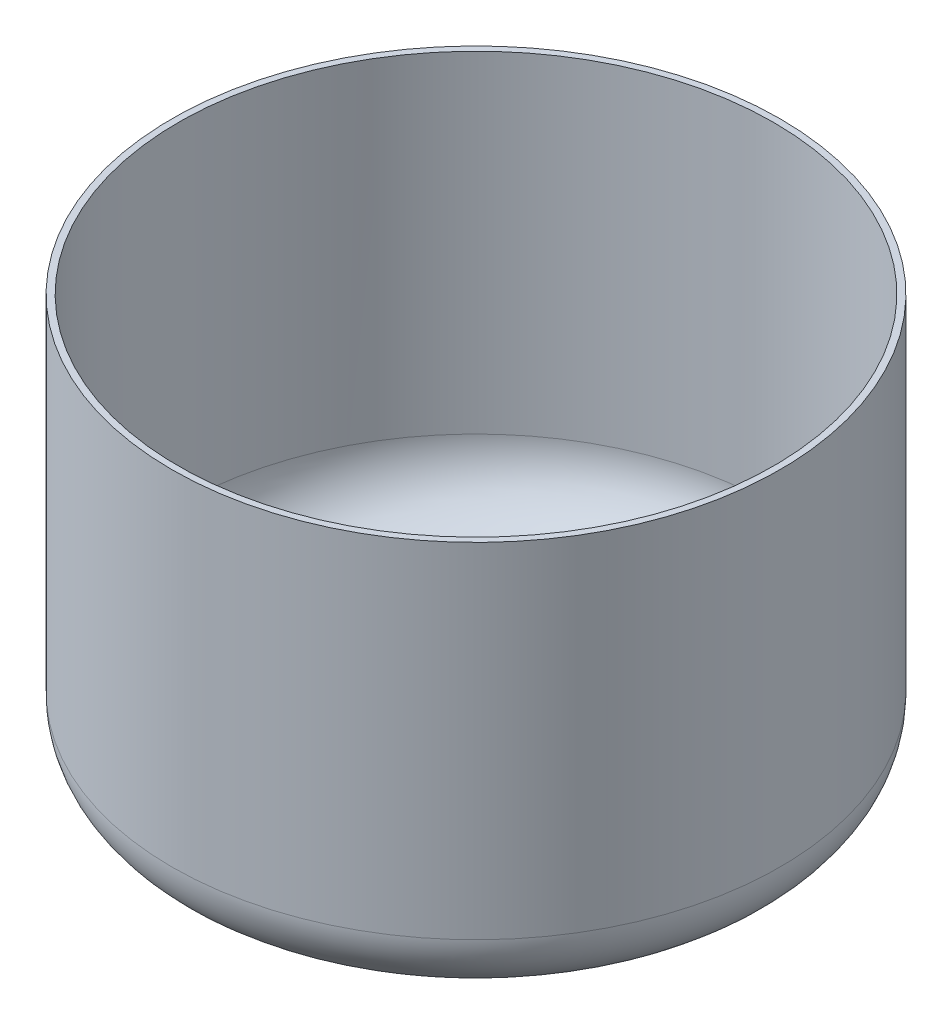
SolidWorks part; units mm, degrees
ref_plane "Front Plane" through (0, 0, 0) normal (0, 0, 1) x (1, 0, 0)
ref_plane "Top Plane" through (0, 0, 0) normal (0, 1, 0) x (1, 0, 0)
ref_plane "Right Plane" through (0, 0, 0) normal (1, 0, 0) x (0, 0, -1)
sketch "Compartment" plane through (0, 0, 0) normal (0, 0, 1) x (1, 0, 0)
  line L3 (120.65, -80) -> (0, -80)
  line L6 (118.11, 81.972) -> (120.65, 81.972)
  line L9 (118.11, 81.972) -> (118.11, -75)
  line L10 (118.11, -75) -> (0, -75)
  line L11 (0, -75) -> (0, -80)
  line L14 (120.65, 81.972) -> (120.65, -80)
  dimension "D1" = 156.972
  dimension "D2" = 2.54
  dimension "D5" = 118.11
  dimension "D6" = 5
  dimension "D9" = 80
ref_axis "Axis1" through (0, 0, 0) along (0, 1, 0)
revolve "Revolve1" add sketch "Compartment" angle 360 about axis through (0, 0, 0) along (0, 1, 0)
sketch "Motor Hole" plane through (0, -80, 0) normal (0, -1, 0) x (1, 0, 0)
  circle A0 centre (0, 0) radius 18.415
  dimension "D1" = 36.83
extrude "Cut-Extrude2" cut sketch "Motor Hole" against normal up to next
sketch "Sketch1" plane through (0, -80, 0) normal (0, -1, 0) x (1, 0, 0)
  circle A0 centre (0, 63.5) radius 3.25
  circle A1 centre (0, -63.5) radius 3.25
  circle A2 centre (63.5, 0) radius 3.25
  circle A3 centre (-63.5, 0) radius 3.25
  dimension "D1" = 6.5
  dimension "D2" = 63.5
  dimension "D3" = 63.5
  dimension "D4" = 63.5
  dimension "D5" = 63.5
  dimension "D6" = 0
  dimension "D7" = 0
extrude "Cut-Extrude3" cut sketch "Sketch1" against normal through all
fillet "Fillet2" radius 25.4 2 edges at (0, -75, -118.11) (0, -80, -120.65)
